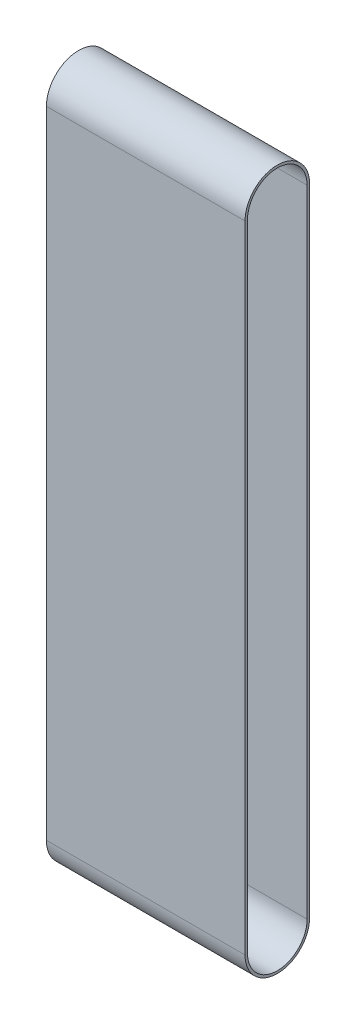
SolidWorks part; units mm, degrees
ref_plane "Front Plane" through (0, 0, 0) normal (0, 0, 1) x (1, 0, 0)
ref_plane "Top Plane" through (0, 0, 0) normal (0, 1, 0) x (1, 0, 0)
ref_plane "Right Plane" through (0, 0, 0) normal (1, 0, 0) x (0, 0, -1)
sketch "Sketch1" plane through (0, 0, 0) normal (1, 0, 0) x (0, 0, -1)
  line L0 (406.4, 1879.6) -> (406.4, 254)
  line L1 (247.65, 254) -> (247.65, 1879.6)
  line L2 (254, 254) -> (254, 1879.6)
  line L3 (412.75, 1879.6) -> (412.75, 254)
  circle A0 centre (330.2, 1879.6) radius 76.2 construction
  circle A1 centre (330.2, 254) radius 76.2 construction
  arc A2 (406.4, 1879.6) -> (254, 1879.6) centre (330.2, 1879.6) ccw construction
  arc A3 (254, 254) -> (406.4, 254) centre (330.2, 254) ccw construction
  arc A4 (406.4, 1879.6) -> (254, 1879.6) centre (330.2, 1879.6) ccw
  arc A5 (254, 254) -> (406.4, 254) centre (330.2, 254) ccw
  arc A6 (412.75, 1879.6) -> (247.65, 1879.6) centre (330.2, 1879.6) ccw
  arc A7 (247.65, 254) -> (412.75, 254) centre (330.2, 254) ccw
  dimension "D1" = 6.35
extrude "Boss-Extrude1" add sketch "Sketch1" along normal mid plane 508
